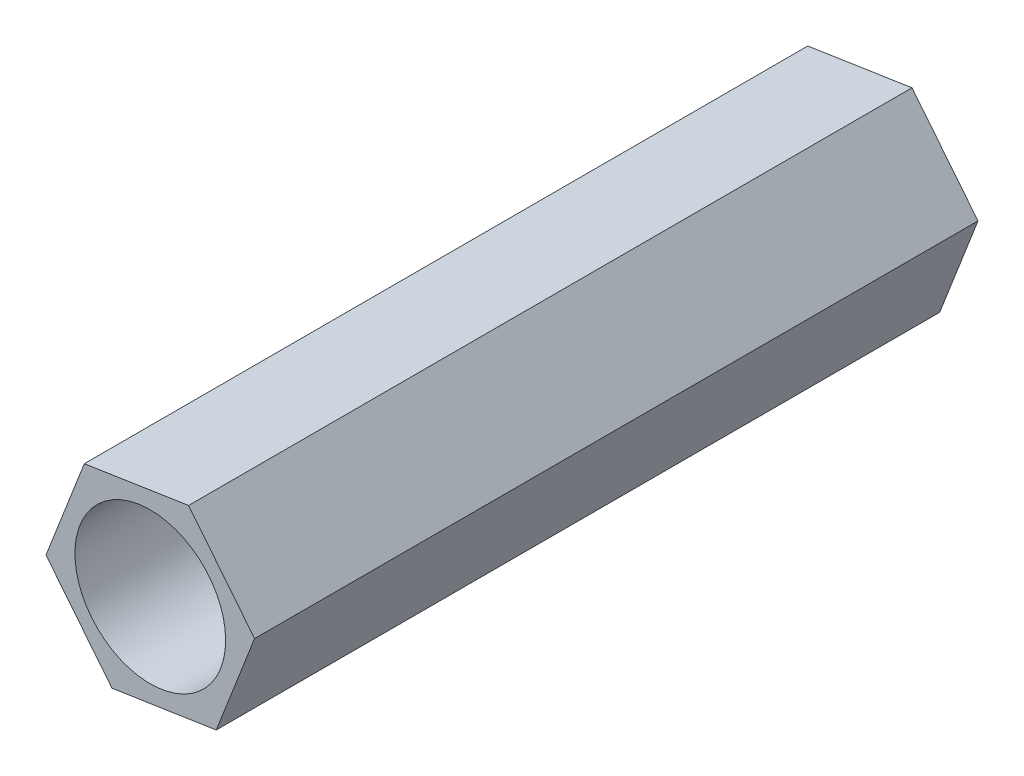
SolidWorks part; units mm, degrees
ref_plane "Front Plane" through (0, 0, 0) normal (0, 0, 1) x (1, 0, 0)
ref_plane "Top Plane" through (0, 0, 0) normal (0, 1, 0) x (1, 0, 0)
ref_plane "Right Plane" through (0, 0, 0) normal (1, 0, 0) x (0, 0, -1)
sketch "Sketch1" plane through (0, 0, 0) normal (0, 0, 1) x (1, 0, 0)
  circle A0 centre (0, 0) radius 1.25
  circle A1 centre (0, 0) radius 1.75
  dimension "D1" = 2.5
  dimension "D2" = 3.5
extrude "Boss-Extrude1" add sketch "Sketch1" along normal blind 12
sketch "Sketch2" plane through (0, 0, 12) normal (0, 0, 1) x (1, 0, 0)
  line L1 (1.0943, -1.3656) -> (1.7298, 0.2649)
  line L2 (1.7298, 0.2649) -> (0.6355, 1.6305)
  line L3 (0.6355, 1.6305) -> (-1.0943, 1.3656)
  line L4 (-1.0943, 1.3656) -> (-1.7298, -0.2649)
  line L5 (-1.7298, -0.2649) -> (-0.6355, -1.6305)
  line L6 (-0.6355, -1.6305) -> (1.0943, -1.3656)
  circle A0 centre (0, 0) radius 1.5155 construction
  circle M7 centre (0, 0) radius 1.75
  dimension "D1" = 1.75
extrude "Cut-Extrude2" cut sketch "Sketch2" against normal blind 12 contours L4 M7 | L3 M7 | L2 M7 | L1 M7 | L6 M7 | L5 M7
